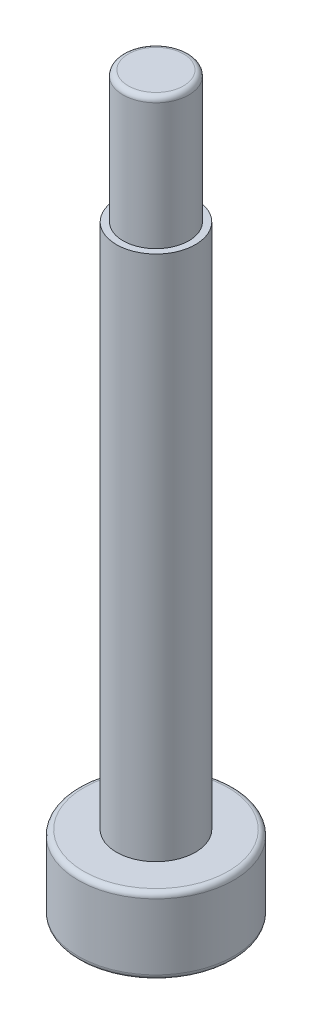
SolidWorks part; units mm, degrees
ref_plane "前视基准面" through (0, 0, 0) normal (0, 0, 1) x (1, 0, 0)
ref_plane "上视基准面" through (0, 0, 0) normal (0, 1, 0) x (1, 0, 0)
ref_plane "右视基准面" through (0, 0, 0) normal (1, 0, 0) x (0, 0, -1)
sketch "草图1" plane through (0, 0, 0) normal (0, 1, 0) x (1, 0, 0)
  circle A0 centre (0, 0) radius 2.95
  dimension "D1" = 5.9
extrude "凸台-拉伸1" add sketch "草图1" along normal blind 2.9
sketch "草图2" plane through (0, 2.9, 0) normal (0, 1, 0) x (1, 0, 0)
  circle A0 centre (0, 0) radius 1.5
  dimension "D1" = 3
extrude "凸台-拉伸2" add sketch "草图2" along normal blind 20
sketch "草图3" plane through (0, 22.9, 0) normal (0, 1, 0) x (1, 0, 0)
  circle A0 centre (0, 0) radius 1.25
  dimension "D1" = 2.5
extrude "凸台-拉伸3" add sketch "草图3" along normal blind 5
sketch "草图4" plane through (0, 0, 0) normal (0, -1, 0) x (1, 0, 0)
  line L1 (2.2473, -0.532) -> (1.5844, 1.6802)
  line L2 (1.5844, 1.6802) -> (-0.6629, 2.2122)
  line L3 (-0.6629, 2.2122) -> (-2.2473, 0.532)
  line L4 (-2.2473, 0.532) -> (-1.5844, -1.6802)
  line L5 (-1.5844, -1.6802) -> (0.6629, -2.2122)
  line L6 (0.6629, -2.2122) -> (2.2473, -0.532)
  circle A0 centre (0, 0) radius 2 construction
  dimension "D1" = 4
extrude "切除-拉伸1" cut sketch "草图4" against normal blind 2
fillet "圆角1" radius 0.2 3 edges at (0, 0, 2.95) (0, 2.9, 2.95) (0, 27.9, 1.25)
